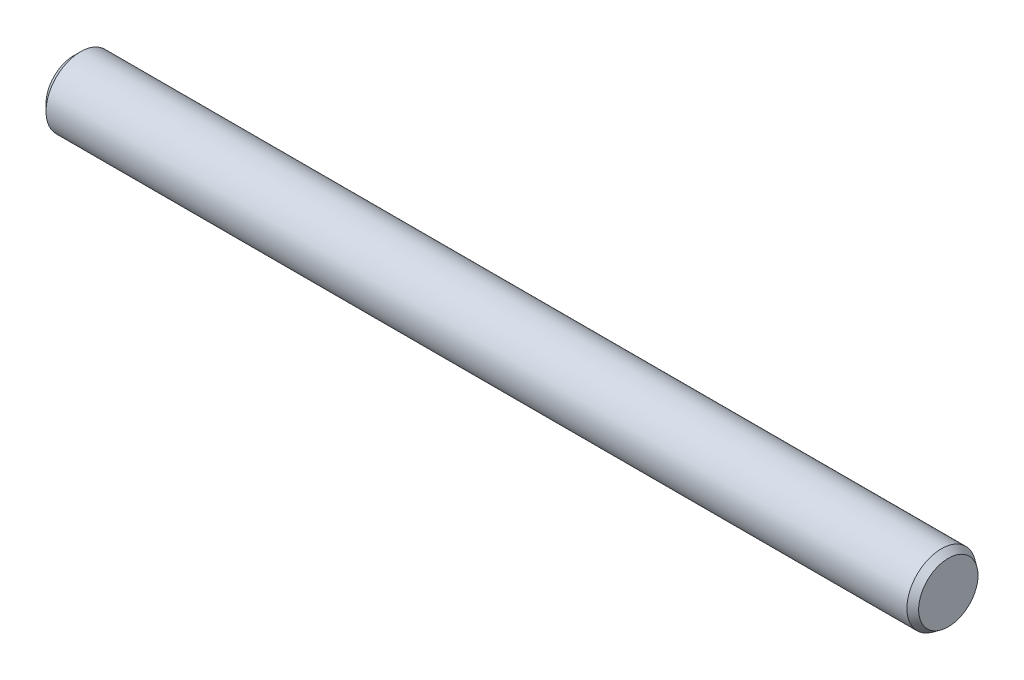
SolidWorks part; units mm, degrees
ref_plane "Plan de face" through (0, 0, 0) normal (0, 0, 1) x (1, 0, 0)
ref_plane "Plan de dessus" through (0, 0, 0) normal (0, 1, 0) x (1, 0, 0)
ref_plane "Plan de droite" through (0, 0, 0) normal (1, 0, 0) x (0, 0, -1)
ref_plane "Plan1" through (12.8, 0, 0) normal (1, 0, 0) x (0, 0, -1)
sketch "Esquisse2" plane through (12.8, 0, 0) normal (1, 0, 0) x (0, 0, -1)
  circle A0 centre (59.3362, -39.1907) radius 1.5
  dimension "D1" = 3
extrude "Boss.-Extru.1" add sketch "Esquisse2" against normal blind 38
chamfer "Chanfrein4" distance 0.3 angle 35 1 edges at (12.8, -39.1907, -60.8362)
chamfer "Chanfrein5" distance 0.3 angle 45 1 edges at (-25.2, -39.1907, -60.8362)
